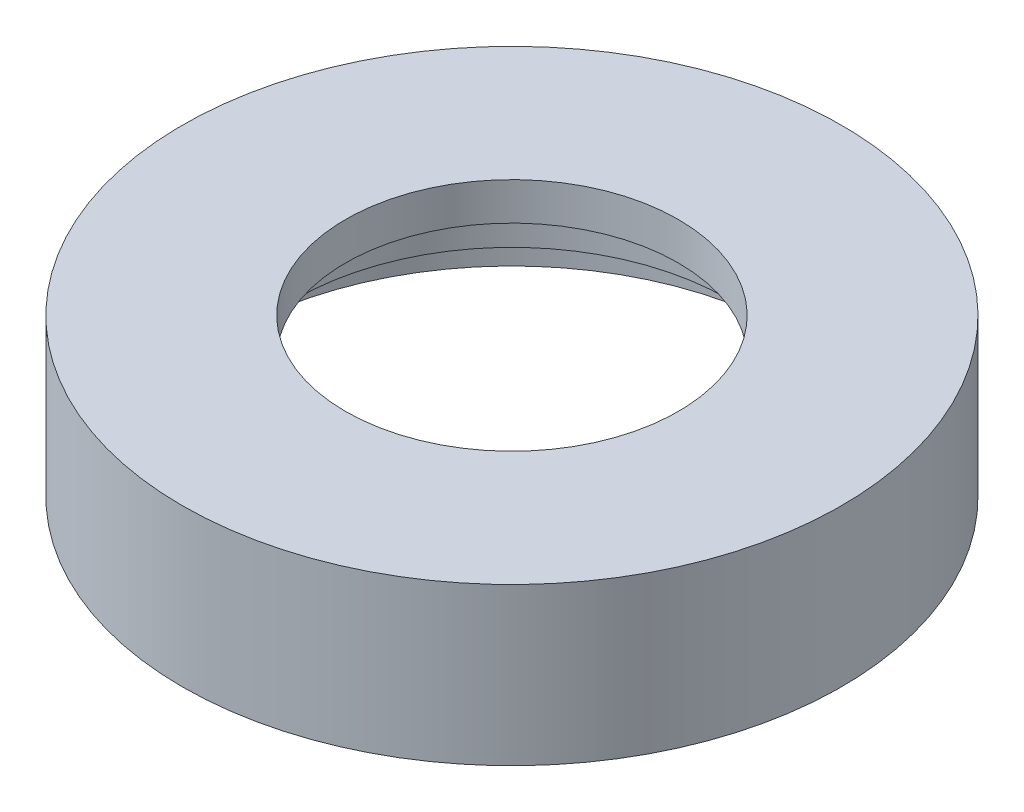
SolidWorks part; units mm, degrees
other "Markup1"
sketch "Sketch2" plane through (-52.5, 0, -52.5) normal (0, 1, 0) x (-1, 0, 0)
ref_plane "Front Plane" through (0, 0, 0) normal (1, 0, 0) x (0, 1, 0)
ref_plane "Top Plane" through (0, 0, 0) normal (0, 0, 1) x (0, 1, 0)
ref_plane "Right Plane" through (0, 0, 0) normal (0, 1, 0) x (-1, 0, 0)
sketch "Sketch1" plane through (0, 0, 0) normal (0, 1, 0) x (-1, 0, 0)
  circle A0 centre (0, 0) radius 52.5
  dimension "D1" = 105
extrude "Boss-Extrude1" add sketch "Sketch1" along normal mid plane 25
sketch "Sketch3" plane through (0, -12.5, 0) normal (0, -1, 0) x (1, 0, 0)
  circle A0 centre (0, 0) radius 45
  dimension "D1" = 90
extrude "Cut-Extrude1" cut sketch "Sketch3" against normal blind 10
sketch "Sketch4" plane through (0, -2.5, 0) normal (0, -1, 0) x (1, 0, 0)
  circle A0 centre (0, 0) radius 34.5
  dimension "D1" = 69
extrude "Cut-Extrude2" cut sketch "Sketch4" against normal blind 9
sketch "Sketch5" plane through (0, 6.5, 0) normal (0, -1, 0) x (1, 0, 0)
  circle A0 centre (0, 0) radius 26.5
  dimension "D1" = 53
extrude "Cut-Extrude3" cut sketch "Sketch5" against normal blind 22
